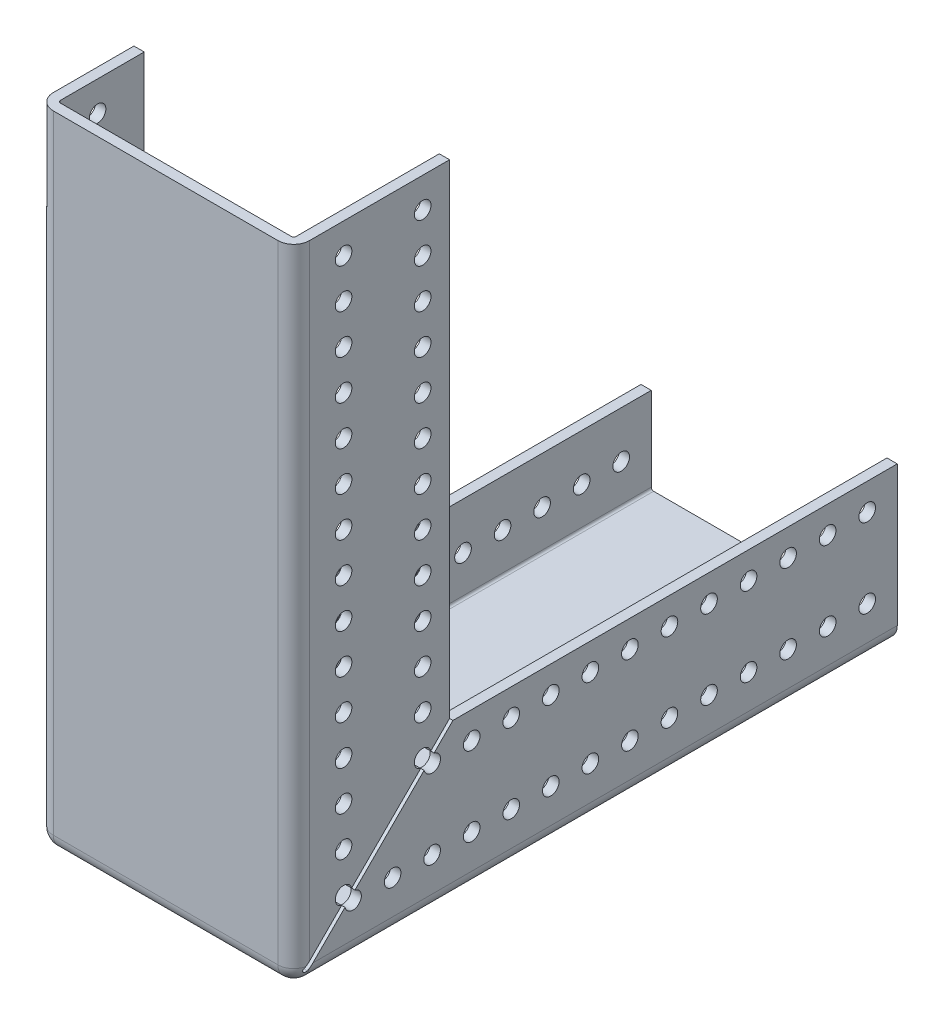
SolidWorks part; units mm, degrees
ref_plane "Front Plane" through (0, 0, 0) normal (0, 0, 1) x (1, 0, 0)
ref_plane "Top Plane" through (0, 0, 0) normal (0, 1, 0) x (1, 0, 0)
ref_plane "Right Plane" through (0, 0, 0) normal (1, 0, 0) x (0, 0, -1)
sketch "Sketch1" plane through (0, 0, 0) normal (0, 1, 0) x (1, 0, 0)
  line L1 (0, 0) -> (82.296, 0)
  line L2 (0, 0) -> (0, 193.802)
  line L3 (0, 193.802) -> (82.296, 193.802)
  line L4 (82.296, 0) -> (82.296, 193.802)
extrude "Boss-Extrude1" add sketch "Sketch1" along normal blind 206.502
sketch "Sketch2" plane through (0, 206.502, 0) normal (0, 1, 0) x (1, 0, 0)
  line L4 (82.296, 193.802) -> (0, 193.802) construction
  line L5 (3.302, 193.802) -> (78.994, 193.802)
  line L8 (3.302, 190.5) -> (3.302, 3.302)
  line L9 (3.302, 3.302) -> (78.994, 3.302)
  line L10 (78.994, 3.302) -> (78.994, 190.5)
  line L11 (78.994, 190.5) -> (3.302, 190.5)
  line L12 (3.302, 193.802) -> (3.302, 3.302)
  line L13 (3.302, 3.302) -> (78.994, 3.302)
  line L14 (78.994, 3.302) -> (78.994, 193.802)
  dimension "D1" = 3.302
extrude "Cut-Extrude1" cut sketch "Sketch2" against normal blind 203.2
sketch "Sketch3" plane through (0, 0, 0) normal (-1, 0, 0) x (0, 0, 1)
  line L1 (-193.802, 206.502) -> (-30.988, 206.502)
  line L2 (-193.802, 206.502) -> (-193.802, 30.988)
  line L3 (-193.802, 30.988) -> (-30.988, 30.988)
  line L4 (-30.988, 206.502) -> (-30.988, 30.988)
extrude "Cut-Extrude2" cut sketch "Sketch3" against normal up to next
sketch "Sketch4" plane through (82.296, 0, 0) normal (1, 0, 0) x (0, 0, -1)
  line L1 (193.802, 206.502) -> (50.038, 206.502)
  line L2 (193.802, 206.502) -> (193.802, 50.038)
  line L3 (193.802, 50.038) -> (50.038, 50.038)
  line L4 (50.038, 206.502) -> (50.038, 50.038)
extrude "Cut-Extrude4" cut sketch "Sketch4" against normal up to next
fillet "Fillet1" radius 0.762 5 edges at (78.994, 3.302, -98.552) (78.994, 104.902, -3.302) (3.302, 3.302, -98.552) (3.302, 104.902, -3.302) (41.148, 3.302, -3.302)
fillet "Fillet2" radius 5.08 5 edges at (82.296, 103.251, 0) (0, 0, -96.901) (0, 103.251, 0) (41.148, 0, 0) (82.296, 0, -96.901)
sketch "Sketch5" plane through (82.296, 0, 0) normal (1, 0, 0) x (0, 0, -1)
  line L0 (4.064, 4.064) -> (57.9288, 57.9288) construction
  line L1 (3.5252, 4.6028) -> (57.39, 58.4676)
  line L2 (4.6028, 3.5252) -> (58.4676, 57.39)
  arc A0 (3.5252, 4.6028) -> (4.6028, 3.5252) centre (4.064, 4.064) ccw
  arc A1 (58.4676, 57.39) -> (57.39, 58.4676) centre (57.9288, 57.9288) ccw
  point P4 (30.9964, 30.9964)
extrude "Cut-Extrude6" cut sketch "Sketch5" against normal through all
ref_plane "Plane1" through (0, 0, 0) normal (0, 0.7071, 0.7071) x (1, 0, 0)
sketch "Sketch6" plane through (82.296, 0, 0) normal (1, 0, 0) x (0, 0, -1)
  circle A0 centre (184.15, 41.402) radius 2.667
  circle A1 centre (171.45, 41.402) radius 2.667
  circle A2 centre (158.75, 41.402) radius 2.667
  circle A3 centre (146.05, 41.402) radius 2.667
  circle A4 centre (133.35, 41.402) radius 2.667
  circle A5 centre (120.65, 41.402) radius 2.667
  circle A6 centre (107.95, 41.402) radius 2.667
  circle A7 centre (95.25, 41.402) radius 2.667
  circle A8 centre (82.55, 41.402) radius 2.667
  circle A9 centre (69.85, 41.402) radius 2.667
  circle A10 centre (57.15, 41.402) radius 2.667
  circle A11 centre (44.45, 41.402) radius 2.667
  circle A12 centre (31.75, 41.402) radius 2.667 [skipped]
  circle A13 centre (19.05, 41.402) radius 2.667 [skipped]
  circle A14 centre (171.45, 16.002) radius 2.667
  circle A15 centre (158.75, 16.002) radius 2.667
  circle A16 centre (146.05, 16.002) radius 2.667
  circle A17 centre (133.35, 16.002) radius 2.667
  circle A18 centre (120.65, 16.002) radius 2.667
  circle A19 centre (107.95, 16.002) radius 2.667
  circle A20 centre (95.25, 16.002) radius 2.667
  circle A21 centre (82.55, 16.002) radius 2.667
  circle A22 centre (69.85, 16.002) radius 2.667
  circle A23 centre (57.15, 16.002) radius 2.667
  circle A24 centre (44.45, 16.002) radius 2.667
  circle A25 centre (31.75, 16.002) radius 2.667
  circle A26 centre (19.05, 16.002) radius 2.667
  circle A27 centre (184.15, 16.002) radius 2.667
  circle A28 centre (196.85, 16.002) radius 2.667
  circle A29 centre (196.85, 41.402) radius 2.667
  dimension "D3" = 2
  dimension "D1" = 14
  dimension "D2" = 2
extrude "Cut-Extrude7" cut sketch "Sketch6" against normal blind 199.898
mirror "Mirror1" about plane through (0, 0, 0) normal (0, 0.7071, 0.7071) of "Cut-Extrude7"
